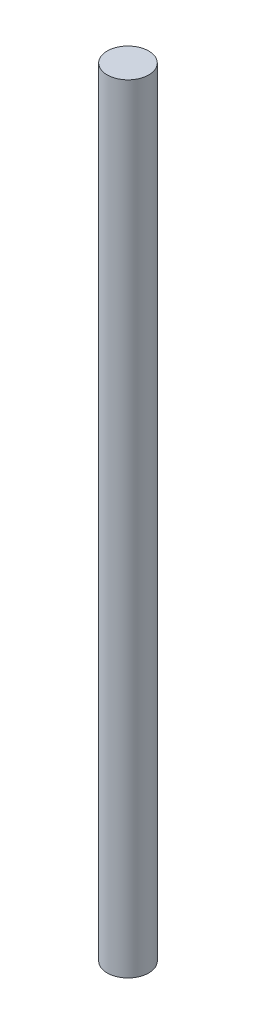
SolidWorks part; units mm, degrees
ref_plane "Front Plane" through (0, 0, 0) normal (0, 0, 1) x (1, 0, 0)
ref_plane "Top Plane" through (0, 0, 0) normal (0, 1, 0) x (1, 0, 0)
ref_plane "Right Plane" through (0, 0, 0) normal (1, 0, 0) x (0, 0, -1)
sketch "Sketch1" plane through (0, 0, 0) normal (0, 1, 0) x (1, 0, 0)
  circle A0 centre (0, 0) radius 4
  dimension "D1" = 8
extrude "Boss-Extrude1" add sketch "Sketch1" along normal blind 150
